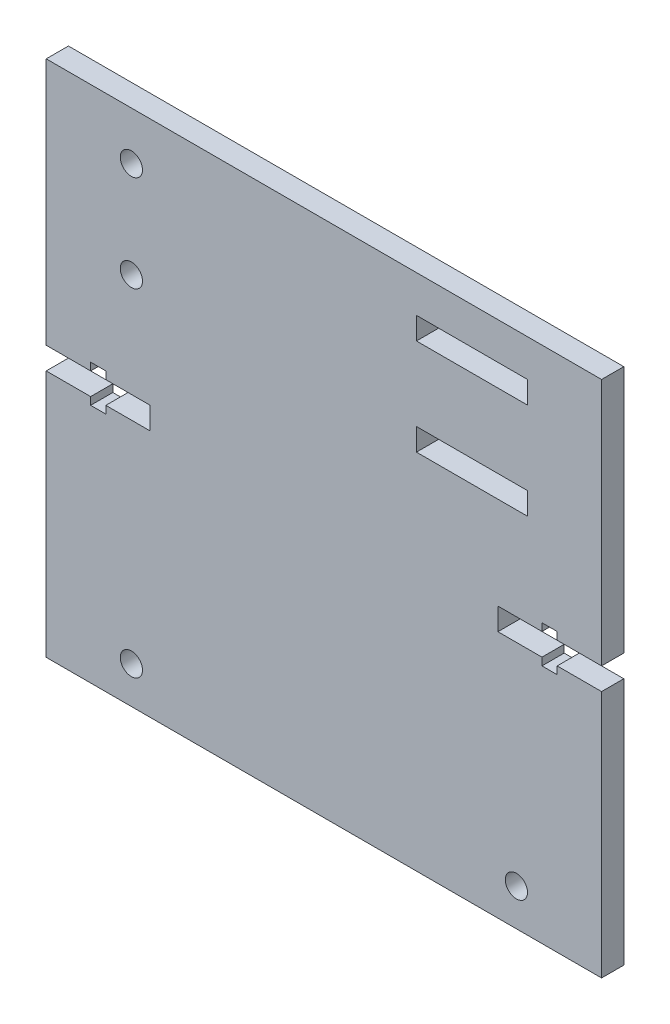
SolidWorks part; units mm, degrees
ref_plane "Front Plane" through (0, 0, 0) normal (0, 0, 1) x (1, 0, 0)
ref_plane "Top Plane" through (0, 0, 0) normal (0, 1, 0) x (1, 0, 0)
ref_plane "Right Plane" through (0, 0, 0) normal (1, 0, 0) x (0, 0, -1)
sketch "Esquisse1" plane through (0, 0, 0) normal (0, 0, 1) x (1, 0, 0)
  line L0 (-0.1837, 14.1633) -> (14.8163, 14.1633)
  line L1 (-50.1837, 32.1633) -> (24.8163, 32.1633)
  line L2 (-50.1837, 32.1633) -> (-50.1837, -37.8367)
  line L3 (-50.1837, -37.8367) -> (24.8163, -37.8367)
  line L4 (24.8163, 32.1633) -> (24.8163, -37.8367)
  line L5 (-0.1837, 14.1633) -> (-0.1837, 11.1633)
  line L6 (-0.1837, 11.1633) -> (14.8163, 11.1633)
  line L7 (14.8163, 14.1633) -> (14.8163, 11.1633)
  line L9 (-0.1837, 27.1633) -> (14.8163, 27.1633)
  line L10 (-0.1837, 27.1633) -> (-0.1837, 24.1633)
  line L11 (-0.1837, 24.1633) -> (14.8163, 24.1633)
  line L12 (14.8163, 27.1633) -> (14.8163, 24.1633)
  circle A0 centre (-38.6837, 25.6633) radius 1.5
  circle A1 centre (-38.6837, 12.6633) radius 1.5
  circle A3 centre (-38.6837, -32.8367) radius 1.5
  circle A4 centre (13.3163, -32.8367) radius 1.5
  point P21 (13.3163, -32.8367)
  dimension "D3" = 11.5
  dimension "D6" = 1.5
  dimension "D7" = 10
  dimension "D10" = 5
  dimension "D11" = 1.5
  dimension "D1" = 75
  dimension "D2" = 70
  dimension "D4" = 3
  dimension "D5" = 5
  dimension "D8" = 11.5
  dimension "D9" = 10
extrude "Boss.-Extru.1" add sketch "Esquisse1" along normal blind 3
sketch "Esquisse2" plane through (0, 0, 0) normal (0, 0, 1) x (1, 0, 0)
  line L0 (24.8163, -1.3367) -> (18.8163, -1.3367)
  line L1 (24.8163, -37.8367) -> (24.8163, 32.1633) construction
  line L2 (18.8163, -1.3367) -> (18.8163, -0.3117)
  line L3 (18.8163, -0.3117) -> (16.7663, -0.3117)
  line L4 (16.7663, -0.3117) -> (16.7663, -1.3367)
  line L5 (16.7663, -1.3367) -> (10.8163, -1.3367)
  line L6 (10.8163, -1.3367) -> (10.8163, -4.3367)
  line L7 (10.8163, -4.3367) -> (16.7663, -4.3367)
  line L8 (16.7663, -4.3367) -> (16.7663, -5.3617)
  line L9 (16.7663, -5.3617) -> (18.8163, -5.3617)
  line L10 (18.8163, -5.3617) -> (18.8163, -4.3367)
  line L11 (18.8163, -4.3367) -> (24.8163, -4.3367)
  line L12 (24.8163, -1.3367) -> (24.8163, -4.3367)
  line L14 (-12.6837, 32.1633) -> (-12.6837, -47.9061) construction
  line L15 (-50.1837, -1.3367) -> (-50.1837, -4.3367)
  line L16 (-44.1837, -4.3367) -> (-50.1837, -4.3367)
  line L17 (-44.1837, -5.3617) -> (-44.1837, -4.3367)
  line L18 (-42.1337, -5.3617) -> (-44.1837, -5.3617)
  line L19 (-42.1337, -4.3367) -> (-42.1337, -5.3617)
  line L20 (-36.1837, -4.3367) -> (-42.1337, -4.3367)
  line L21 (-36.1837, -1.3367) -> (-36.1837, -4.3367)
  line L22 (-42.1337, -1.3367) -> (-36.1837, -1.3367)
  line L23 (-42.1337, -0.3117) -> (-42.1337, -1.3367)
  line L24 (-44.1837, -0.3117) -> (-42.1337, -0.3117)
  line L25 (-44.1837, -1.3367) -> (-44.1837, -0.3117)
  line L26 (-50.1837, -1.3367) -> (-44.1837, -1.3367)
  dimension "D1" = 3
  dimension "D2" = 3
  dimension "D3" = 5.05
  dimension "D4" = 1.025
  dimension "D5" = 1.025
  dimension "D6" = 14
  dimension "D7" = 0
  dimension "D8" = 6
  dimension "D9" = 6
  dimension "D10" = 2.05
  dimension "D11" = 2.05
extrude "Enlèv. mat.-Extru.1" cut sketch "Esquisse2" against normal blind 10 and the other way blind 10
